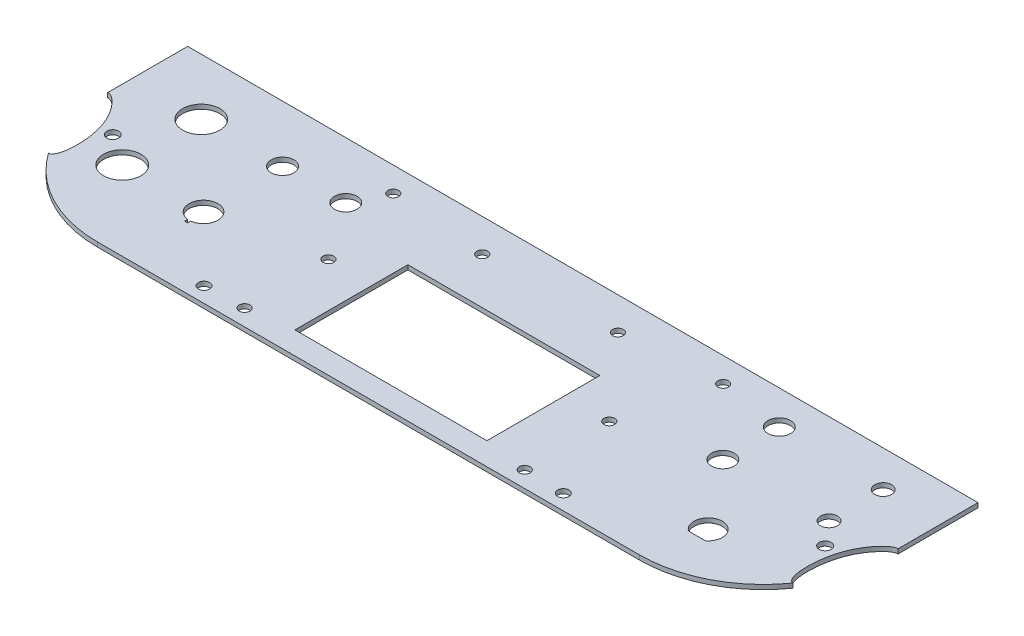
SolidWorks part; units mm, degrees
material "Thornel Mat VMA"
ref_plane "Front Plane" through (0, 0, 0) normal (0, 0, 1) x (1, 0, 0)
ref_plane "Top Plane" through (0, 0, 0) normal (0, 1, 0) x (1, 0, 0)
ref_plane "Right Plane" through (0, 0, 0) normal (1, 0, 0) x (0, 0, -1)
sketch "Sketch1" plane through (0, 0, 0) normal (0, 1, 0) x (1, 0, 0)
  line L13 (-222.25, 0) -> (222.25, 0) construction
  line L14 (222.25, -14.6125) -> (222.25, 36.1875)
  line L15 (222.25, 36.1875) -> (-222.25, 36.1875)
  line L16 (-222.25, -14.6125) -> (-222.25, 36.1875)
  line L18 (0, -95.4736) -> (0, 95.4736) construction
  line L19 (152.4, -84.4625) -> (-152.4, -84.4625)
  arc A0 (222.25, -14.6125) -> (152.4, -84.4625) centre (152.4, -14.6125) cw
  arc A1 (-152.4, -84.4625) -> (-222.25, -14.6125) centre (-152.4, -14.6125) cw
  point P10 (0, 0)
  point P16 (0, 0)
  point P17 (0, -84.4625)
  dimension "D1" = 50.8
  dimension "D2" = 444.5
  dimension "D3" = 304.8
  dimension "D5" = 120.65
  dimension "D6" = 36.1875
extrude "Boss-Extrude1" add sketch "Sketch1" along normal blind 2.54
sketch "Sketch2" plane through (0, 2.54, 0) normal (0, 1, 0) x (1, 0, 0)
  line L1 (53.975, -71.7625) -> (-53.975, -71.7625)
  line L2 (53.975, -71.7625) -> (53.975, -8.2625)
  line L3 (53.975, -8.2625) -> (-53.975, -8.2625)
  line L4 (-53.975, -71.7625) -> (-53.975, -8.2625)
  line L5 (53.975, -71.7625) -> (-53.975, -8.2625) construction
  line L6 (53.975, -8.2625) -> (-53.975, -71.7625) construction
  line L8 (-152.4, -84.4625) -> (152.4, -84.4625) construction
  point P0 (0, -40.0125)
  dimension "D1" = 63.5
  dimension "D2" = 12.7
  dimension "D3" = 107.95
extrude "Cut-Extrude1" cut sketch "Sketch2" against normal through all
sketch "Sketch4" plane through (0, 2.54, 0) normal (0, 1, 0) x (1, 0, 0)
  line L6 (-138.01, -48.0677) -> (-138.01, -49.8125)
  line L12 (-138.01, -49.8125) -> (-136.31, -49.8125)
  line L14 (-136.31, -49.8125) -> (-136.31, -48.0677)
  line L17 (222.25, -14.6125) -> (222.25, 36.1875) construction
  line L18 (222.25, 36.1875) -> (-222.25, 36.1875) construction
  line L19 (-222.25, 36.1875) -> (-222.25, -14.6125) construction
  line L21 (164.1475, -59.0625) -> (154.6225, -59.0625)
  line L22 (-152.4, -84.4625) -> (152.4, -84.4625) construction
  line L54 (87.5424, -0.6073) -> (87.4312, -0.6714)
  circle A0 centre (189.23, 15.8675) radius 4.7625
  circle A2 centre (-137.16, 4.4375) radius 6.35
  circle A3 centre (129.54, 17.1375) radius 6.35
  circle A4 centre (129.54, -14.6125) radius 6.35
  circle A6 centre (189.23, -14.6125) radius 4.7625
  circle A7 centre (-182.88, -40.0125) radius 10.5
  arc A8 (-136.31, -48.0677) -> (-138.01, -48.0677) centre (-137.16, -40.0125) ccw
  circle A9 centre (-182.88, 4.4375) radius 10.5
  arc A12 (164.1475, -59.0625) -> (154.6225, -59.0625) centre (159.385, -52.7125) ccw
  circle A25 centre (-101.6, 4.4375) radius 6.35
  circle A36 centre (-38.131, 17.7452) radius 3.025 construction
  circle A37 centre (-79, -27.9475) radius 3.025 construction
  circle A48 centre (-78.7827, -75.2875) radius 3.025 construction
  circle A49 centre (78.7827, -75.2875) radius 3.025 construction
  circle A51 centre (79, -27.9475) radius 3.025 construction
  arc A72 (85, -6.1987) -> (84.9641, -5.581) centre (79.666, -6.1987) ccw
  circle A73 centre (38.131, 17.7452) radius 3.025 construction
  circle A74 centre (-38.131, 17.7452) radius 3.025
  circle A75 centre (-79, -27.9475) radius 3.025
  circle A76 centre (-78.7827, -75.2875) radius 3.025
  circle A77 centre (78.7827, -75.2875) radius 3.025
  circle A78 centre (79, -27.9475) radius 3.025
  circle A79 centre (38.131, 17.7452) radius 3.025
  point P24 (-137.16, -49.8125)
  dimension "D2" = 12.7
  dimension "D3" = 15.875
  dimension "D11" = 9.8
  dimension "D12" = 16.2
  dimension "D20" = 31.75
  dimension "D25" = 9.525
  dimension "D10" = 21
  dimension "D4" = 31.75
  dimension "D5" = 20.32
  dimension "D6" = 33.02
  dimension "D7" = 59.69
  dimension "D8" = 35.56
  dimension "D9" = 50.8
  dimension "D13" = 39.37
  dimension "D14" = 85.09
  dimension "D15" = 62.865
  dimension "D16" = 31.75
  dimension "D17" = 76.2
  dimension "D18" = 6.35
  dimension "D19" = 1.7
  dimension "D21" = 31.75
sketch "Sketch5" plane through (0, 2.54, 0) normal (0, 1, 0) x (1, 0, 0)
  line L0 (222.25, -14.6125) -> (222.25, 36.1875) construction
  line L1 (0, -1.397) -> (0, 1.397) construction
  arc A0 (152.4, -84.4625) -> (222.25, -14.6125) centre (152.4, -14.6125) ccw construction
  spline S0 degree 3 poles (235.1366, 7.4285) (207.1804, -83.7935) (202.3049, -25.2668) (235.1366, 7.4285) (207.1804, -83.7935) (202.3049, -25.2668) knots -1 -0.674196 -0.483325 0 0.325804 0.516675 1 1.325804 1.516675 2 only from (209.4403, -54.9291) to (209.4403, -54.9291)
  spline S1 degree 3 poles (-235.1366, 7.4285) (-207.1804, -83.7935) (-202.3049, -25.2668) (-235.1366, 7.4285) (-207.1804, -83.7935) (-202.3049, -25.2668) knots -1 -0.674196 -0.483325 0 0.325804 0.516675 1 1.325804 1.516675 2 only from (-209.4403, -54.9291) to (-209.4403, -54.9291)
  line M8 (-222.25, 36.1875) -> (-222.25, -14.6125)
  arc M9 (-222.25, -14.6125) -> (-152.4, -84.4625) centre (-152.4, -14.6125) ccw
extrude "Cut-Extrude4" cut sketch "Sketch5" against normal up to surface (2.54 mm away) contours S1 M9 M8 | S0 up to face at (0, 0, 40.0125)
extrude "Cut-Extrude3" cut sketch "Sketch4" against normal through all contours A25 | A77
sketch "Sketch6" plane through (0, 0, 0) normal (0, -1, 0) x (1, 0, 0)
  line L0 (0, -1.397) -> (0, 1.397) construction
  circle A0 centre (92.7683, -22.3351) radius 3.0138
  circle A1 centre (101.0562, 75.863) radius 3.1768
  circle A2 centre (200.3502, 27.8837) radius 3.3788
  circle A3 centre (-92.7683, -22.3351) radius 3.0138
  circle A4 centre (-200.3502, 27.8837) radius 3.3788
  circle A5 centre (-101.0562, 75.863) radius 3.1768
extrude "Cut-Extrude5" cut sketch "Sketch6" against normal through all
